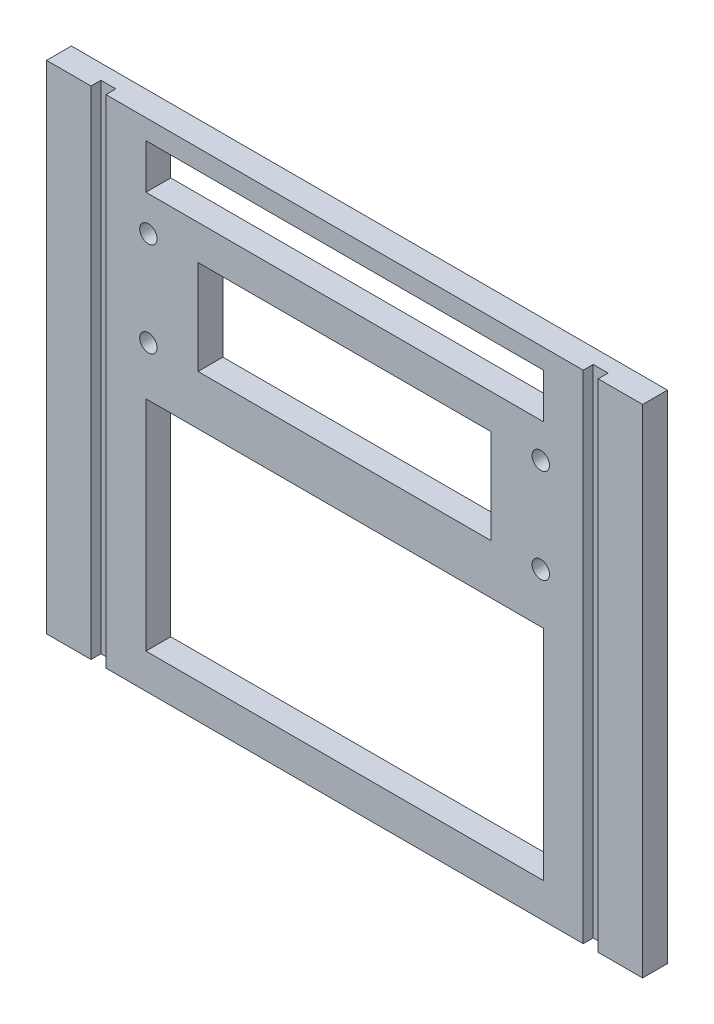
SolidWorks part; units mm, degrees
ref_plane "前视基准面" through (0, 0, 0) normal (0, 0, 1) x (1, 0, 0)
ref_plane "上视基准面" through (0, 0, 0) normal (0, 1, 0) x (1, 0, 0)
ref_plane "右视基准面" through (0, 0, 0) normal (1, 0, 0) x (0, 0, -1)
other "Configuration Table"
sketch "草图1" plane through (0, 0, 0) normal (0, 0, 1) x (1, 0, 0)
  line L1 (0, 0) -> (120, 0)
  line L2 (0, 0) -> (0, 100)
  line L3 (0, 100) -> (120, 100)
  line L4 (120, 0) -> (120, 100)
  dimension "D1" = 120
  dimension "D2" = 100
extrude "凸台-拉伸1" add sketch "草图1" along normal blind 5
sketch "草图2" plane through (0, 0, 5) normal (0, 0, 1) x (1, 0, 0)
  line L0 (120, 100) -> (0, 100) construction
  line L1 (8.95, 100) -> (11.95, 100)
  line L2 (8.95, 100) -> (8.95, 0)
  line L3 (8.95, 0) -> (11.95, 0)
  line L4 (11.95, 100) -> (11.95, 0)
  line L5 (0, 0) -> (120, 0) construction
  line L6 (0, 100) -> (0, 0) construction
  line L7 (108.05, 0) -> (111.05, 0)
  line L8 (108.05, 0) -> (108.05, 100)
  line L9 (108.05, 100) -> (111.05, 100)
  line L10 (111.05, 0) -> (111.05, 100)
  line L11 (120, 0) -> (120, 100) construction
  dimension "D1" = 3
  dimension "D2" = 3
  dimension "D3" = 8.95
  dimension "8.0" = 8.95
extrude "切除-拉伸1" cut sketch "草图2" against normal blind 2
sketch "草图3" plane through (0, 0, 5) normal (0, 0, 1) x (1, 0, 0)
  line L0 (11.95, 70.5) -> (108.05, 70.5) construction
  line L1 (11.95, 0) -> (11.95, 100) construction
  line L2 (108.05, 100) -> (108.05, 0) construction
  line L3 (11.95, 0) -> (108.05, 0) construction
  line L4 (20.5, 80) -> (99.5, 80) construction
  line L5 (108.05, 100) -> (11.95, 100) construction
  line L6 (20, 51) -> (100, 51)
  line L7 (20, 51) -> (20, 7)
  line L8 (20, 7) -> (100, 7)
  line L9 (100, 51) -> (100, 7)
  line L10 (20, 87) -> (100, 87)
  line L11 (20, 87) -> (20, 96)
  line L12 (20, 96) -> (100, 96)
  line L13 (100, 87) -> (100, 96)
  line L15 (30.5, 80) -> (89.5, 80)
  line L16 (30.5, 80) -> (30.5, 61)
  line L17 (30.5, 61) -> (89.5, 61)
  line L18 (89.5, 80) -> (89.5, 61)
  circle A0 centre (20.5, 80) radius 1.75
  circle A1 centre (20.5, 61) radius 1.75
  circle A2 centre (99.5, 80) radius 1.75
  circle A3 centre (99.5, 61) radius 1.75
  point P16 (60, 80)
  point P17 (60, 70.5)
  point P22 (60, 51)
  dimension "D2" = 3.5
  dimension "D1" = 70.5
  dimension "D3" = 9.5
  dimension "D4" = 9.5
  dimension "D5" = 79
  dimension "D6" = 80
  dimension "D7" = 7
  dimension "D8" = 10
  dimension "D9" = 4
  dimension "D10" = 7
  dimension "D11" = 10
  dimension "D12" = 10
  dimension "D13" = 10
extrude "切除-拉伸2" cut sketch "草图3" against normal through all
